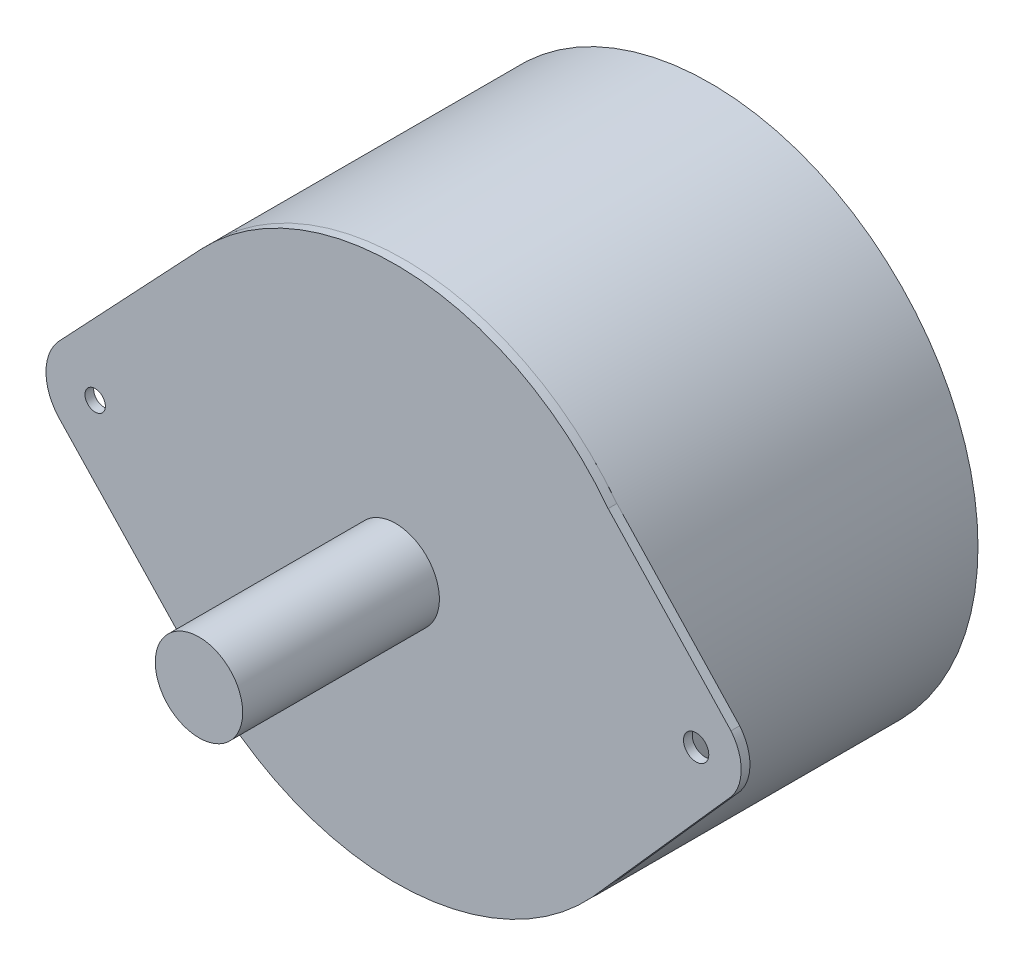
SolidWorks part; units mm, degrees
material "1.0715 (11SMn30)"
ref_plane "Спереди" through (0, 0, 0) normal (0, 0, 1) x (1, 0, 0)
ref_plane "Сверху" through (0, 0, 0) normal (0, 1, 0) x (1, 0, 0)
ref_plane "Справа" through (0, 0, 0) normal (1, 0, 0) x (0, 0, -1)
sketch "Эскиз1" plane through (0, 0, 0) normal (0, 0, 1) x (1, 0, 0)
  circle A0 centre (-5.3039, -8.4878) radius 24.5
  dimension "D1" = 49
extrude "Бобышка-Вытянуть1" add sketch "Эскиз1" along normal blind 28
sketch "Эскиз5" plane through (0, 0, 28) normal (0, 0, 1) x (1, 0, 0)
  line L0 (-5.3039, -8.4878) -> (37.1033, -8.0489) construction
  line L1 (-5.3039, -8.4878) -> (-32.8039, -8.4878) construction
  line L2 (-36.2417, -5.5841) -> (-23.0955, 8.3558)
  line L3 (-36.1464, -11.5007) -> (-23.7007, -24.6681)
  line L4 (25.1115, -11.1241) -> (12.7049, -25.099)
  line L5 (25.3854, -5.5841) -> (14.1471, 6.4088)
  arc A0 (-36.1464, -11.5007) -> (-36.2417, -5.5841) centre (-32.8039, -8.4878) cw
  arc A1 (25.1115, -11.1241) -> (25.3854, -5.5841) centre (22.1961, -8.2032) ccw
  circle A2 centre (-5.3039, -8.4878) radius 24.5 construction
  arc A3 (-23.7007, -24.6681) -> (12.7049, -25.099) centre (-5.3039, -8.4878) ccw
  arc A4 (-23.0955, 8.3558) -> (14.1471, 6.4088) centre (-5.3006, -8.4258) cw
  dimension "D1" = 27.5
  dimension "D2" = 27.5
extrude "Бобышка-Вытянуть3" add sketch "Эскиз5" along normal blind 0.8 separate body
sketch "Эскиз6" plane through (0, 0, 28.8) normal (0, 0, 1) x (1, 0, 0)
  line L0 (-32.8039, -8.4878) -> (31.841, -8.4878) construction
  line L1 (-5.3006, 16.034) -> (-5.3006, -33.8973) construction
  circle A0 centre (-32.8039, -8.4878) radius 0.9338
  circle A1 centre (22.1994, -8.4878) radius 1.1579
  arc A3 (14.1471, 6.4088) -> (-23.0955, 8.3558) centre (-5.3006, -8.4258) ccw construction
  dimension "D1" = 27.5
  dimension "D2" = 27.5032
extrude "Вырез-Вытянуть4" cut sketch "Эскиз6" against normal blind 0.8
sketch "Эскиз7" plane through (0, 0, 28.8) normal (0, 0, 1) x (1, 0, 0)
  line L0 (-32.8039, -8.4878) -> (28.3401, -8.4878) construction
  line L1 (-5.3006, 16.034) -> (-5.3006, -34.542) construction
  arc A0 (14.1471, 6.4088) -> (-23.0955, 8.3558) centre (-5.3006, -8.4258) ccw construction
  circle A1 centre (-5.3006, -8.4878) radius 4
  dimension "D1" = 8
extrude "Бобышка-Вытянуть4" add sketch "Эскиз7" along normal blind 18
